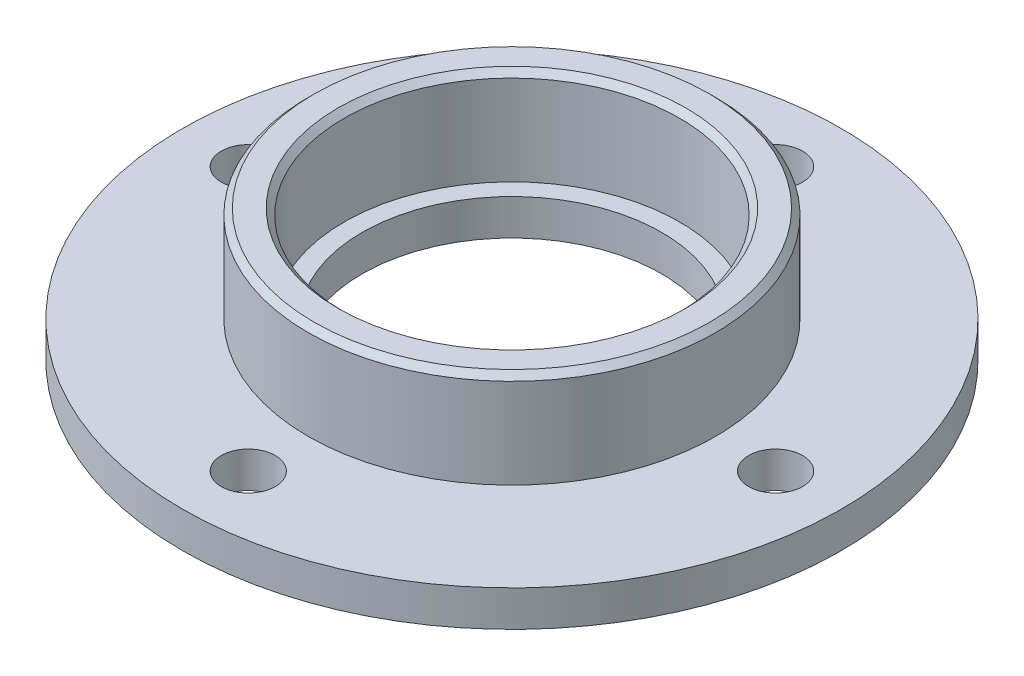
SolidWorks part; units mm, degrees
material "AISI 316 Stainless Steel Sheet (SS)"
ref_plane "Front Plane" through (0, 0, 0) normal (0, 0, 1) x (1, 0, 0)
ref_plane "Top Plane" through (0, 0, 0) normal (0, 1, 0) x (1, 0, 0)
ref_plane "Right Plane" through (0, 0, 0) normal (1, 0, 0) x (0, 0, -1)
sketch "Sketch1" plane through (0, 0, 0) normal (0, 1, 0) x (1, 0, 0)
  line L0 (0, -44.7868) -> (0, 44.7868) construction
  line L1 (-44.2539, 0) -> (44.2539, 0) construction
  circle A0 centre (0, 0) radius 12.5
  circle A1 centre (0, 0) radius 27.5
  circle A2 centre (0, 22) radius 1
  circle A3 centre (22, 0) radius 1
  circle A4 centre (0, -22) radius 1
  circle A5 centre (-22, 0) radius 1
  point P17 (0, 0)
  dimension "D1" = 25
  dimension "D2" = 55
  dimension "D3" = 2
  dimension "D5" = 22
  dimension "D4" = 4
extrude "Boss-Extrude1" add sketch "Sketch1" along normal mid plane 3
sketch "Sketch2" plane through (0, 1.5, 0) normal (0, 1, 0) x (1, 0, 0)
  circle A0 centre (0, 0) radius 14
  circle A1 centre (0, 0) radius 17
  dimension "D1" = 28
  dimension "D2" = 34
extrude "Boss-Extrude2" add sketch "Sketch2" along normal blind 8
chamfer "Chamfer1" distance 0.5 angle 45 2 edges at (0, 9.5, 14) (0, 9.5, 17)
sketch "Sketch5" plane through (0, 1.5, 0) normal (0, 1, 0) x (1, 0, 0)
  point P0 (0, 22)
  point P3 (22, 0)
  point P6 (-22, 0)
  point P9 (0, -22)
hole_wizard "M4 Clearance Hole1" positions "Sketch5" profile "Sketch4" hole size "M4" standard "ANSI Metric"
sketch "Sketch4" plane through (0, 1.5, -22) normal (1, 0, 0) x (0, 0, 1)
  line L0 (0, 0) -> (0, 12.8519)
  line L1 (0, 12.8519) -> (2.25, 11.5)
  line L2 (2.25, 11.5) -> (2.25, 0)
  line L5 (2.25, 0) -> (0, 0)
  line L10 (0, 12.8519) -> (-2.25, 11.5) construction
  line L11 (0, -6.35) -> (0, 107.95) construction
  dimension "Hole Dia." = 4.5
  dimension "Hole Depth" = 11.5
  dimension "Drill Angle" = 118
